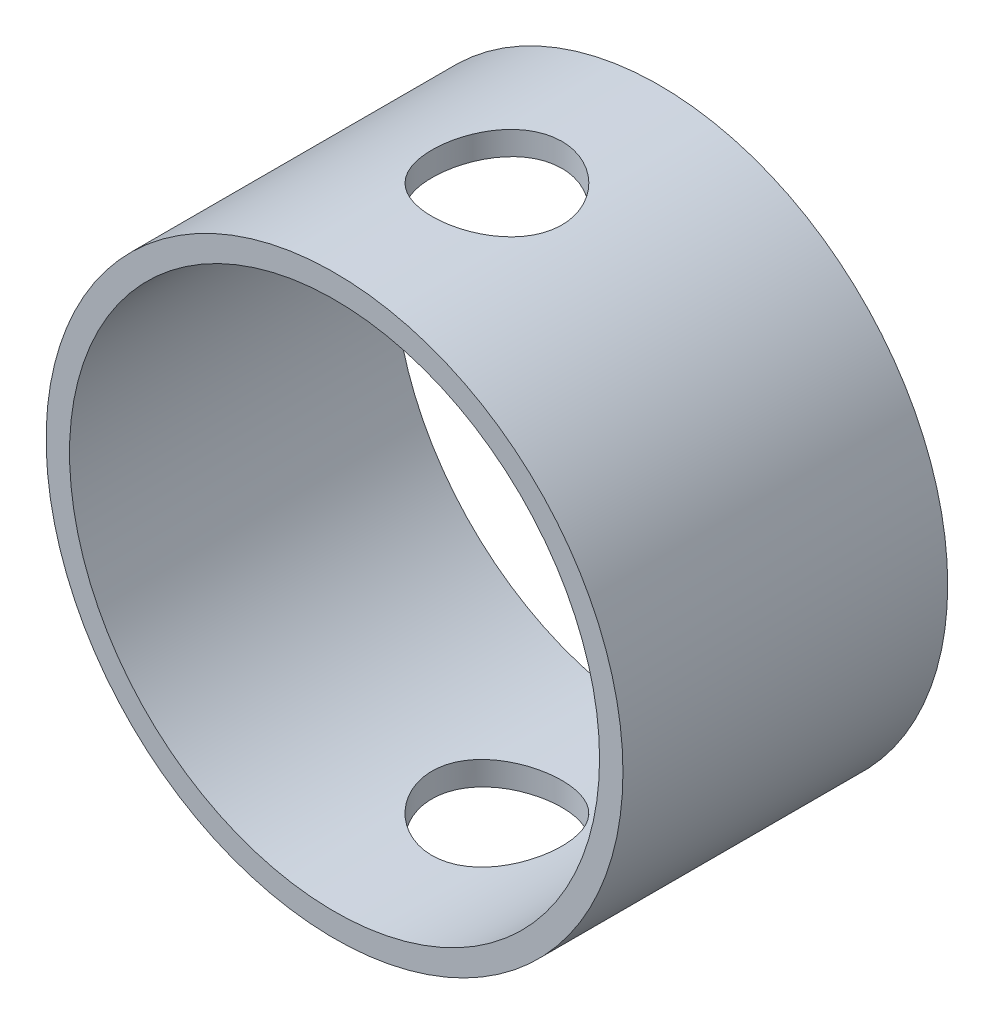
SolidWorks part; units mm, degrees
ref_plane "Front Plane" through (0, 0, 0) normal (0, 0, 1) x (1, 0, 0)
ref_plane "Top Plane" through (0, 0, 0) normal (0, 1, 0) x (1, 0, 0)
ref_plane "Right Plane" through (0, 0, 0) normal (1, 0, 0) x (0, 0, -1)
sketch "Sketch1" plane through (0, 0, 0) normal (0, 0, 1) x (1, 0, 0)
  circle A0 centre (0, 0) radius 233.4
  circle A1 centre (0, 0) radius 254
  dimension "D1" = 466.8
  dimension "D2" = 20.6
extrude "Boss-Extrude1" add sketch "Sketch1" along normal mid plane 286
sketch "Sketch2" plane through (0, 0, 0) normal (0, 1, 0) x (1, 0, 0)
  circle A0 centre (0, 0) radius 57.25
  dimension "D1" = 114.5
extrude "Cut-Extrude1" cut sketch "Sketch2" along normal through all both and the other way through all
